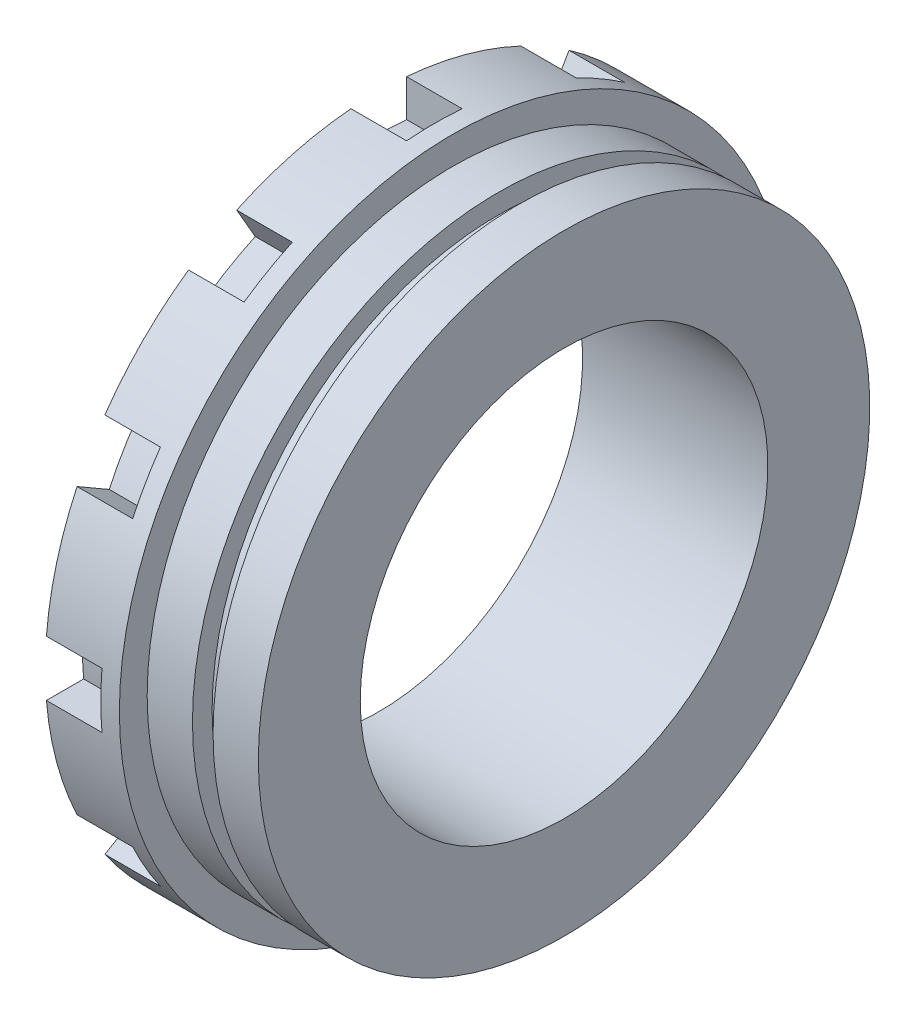
SolidWorks part; units mm, degrees
material "6061-T6 (SS)"
ref_plane "X-Y Datum" through (0, 0, 0) normal (0, 0, 1) x (1, 0, 0)
ref_plane "X-Z Datum" through (0, 0, 0) normal (0, 1, 0) x (1, 0, 0)
ref_plane "Y-Z Datum" through (0, 0, 0) normal (1, 0, 0) x (0, 0, -1)
sketch "Sketch2" plane through (0, 0, 0) normal (0, 0, 1) x (1, 0, 0)
  line L0 (0, 0) -> (0, 29100.2887) construction
  line L1 (0, 0) -> (29100.2887, 0) construction
  line L10 (-22.225, 57.15) -> (-9.525, 57.15)
  line L11 (-9.525, 57.15) -> (-9.525, 52.3875)
  line L12 (-9.525, 52.3875) -> (-1.7653, 52.3875)
  line L13 (-1.7653, 52.3875) -> (-1.7653, 49.022)
  line L14 (-1.7653, 49.022) -> (1.7653, 49.022)
  line L15 (1.7653, 49.022) -> (1.7653, 52.3875)
  line L16 (1.7653, 52.3875) -> (9.525, 52.3875)
  line L17 (9.525, 52.3875) -> (9.525, 34.925)
  line L18 (9.525, 34.925) -> (-22.225, 34.925)
  line L19 (-22.225, 34.925) -> (-22.225, 57.15)
  point P7 (0, 0)
  point P16 (0, 0)
  point P17 (0, 49.022)
  dimension "D1" = 98.044
  dimension "D2" = 69.85
  dimension "D3" = 114.3
  dimension "D4" = 104.775
  dimension "D5" = 3.5306
  dimension "D6" = 12.7
  dimension "D7" = 9.525
  dimension "D8" = 9.525
revolve "Revolve1" add sketch "Sketch2" angle 360 about L1
sketch "Sketch3" plane through (-22.225, 0, 0) normal (-1, 0, 0) x (0, 0, 1)
  line L0 (0, 0) -> (0, 50000) construction
  line L7 (0, 0) -> (50000, 0) construction
  line L8 (-4.7625, 56.9512) -> (-4.7625, 50.5763)
  line L13 (4.7625, 56.9512) -> (4.7625, 50.5763)
  circle A1 centre (0, 0) radius 57.15 construction
  arc A3 (4.7625, 56.9512) -> (-4.7625, 56.9512) centre (0, 0) ccw
  arc A4 (4.7625, 50.5763) -> (-4.7625, 50.5763) centre (0, 0) ccw
  point P5 (0, 57.15)
  point P7 (0, 0)
  circle M3 centre (0, 0) radius 57.15
  dimension "D1" = 57.15
  dimension "D4" = 50.8
  dimension "D2" = 4.7625
  dimension "D3" = 4.7625
  dimension "D5" = 57.15
extrude "Cut-Extrude1" cut sketch "Sketch3" against normal offset from surface (9.525 mm away) 3.175 contours A4 L13 L8 M3
pattern_circular "CirPattern1" count 12 over 360 about axis through (0, 0, 0) along (1, 0, 0) of "Cut-Extrude1"
equation "\"D2@Sketch2\"=2.75"
equation "\"D3@Sketch2\"=4.5"
